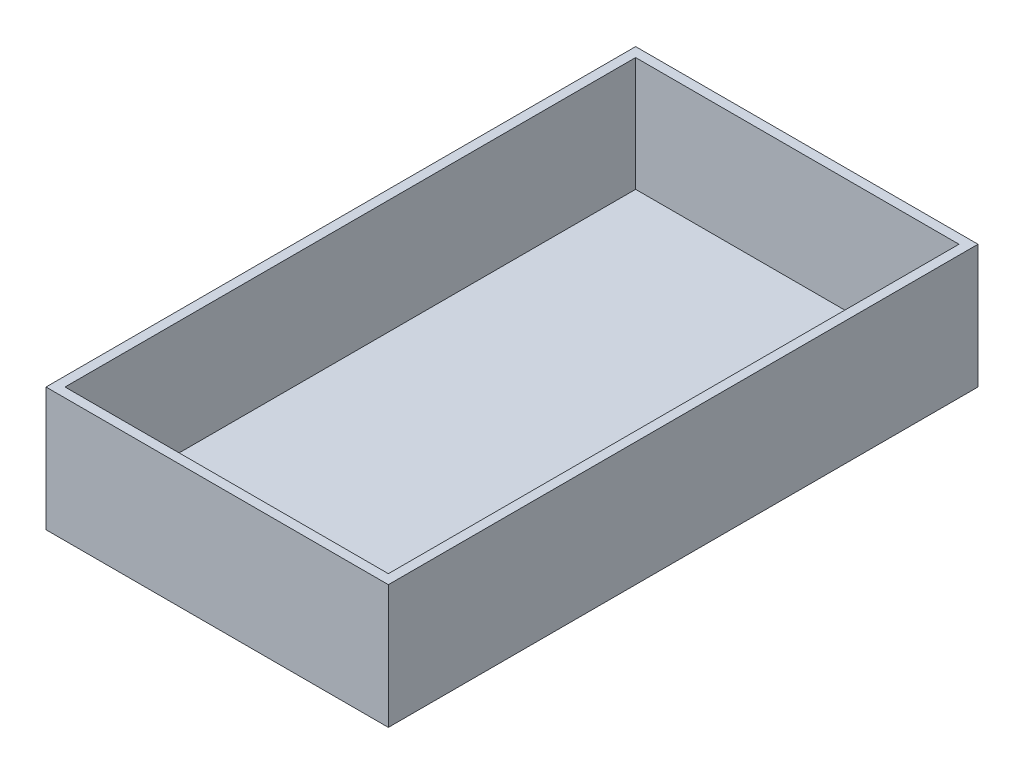
SolidWorks part; units mm, degrees
ref_plane "Front Plane" through (0, 0, 0) normal (0, 0, 1) x (1, 0, 0)
ref_plane "Top Plane" through (0, 0, 0) normal (0, 1, 0) x (1, 0, 0)
ref_plane "Right Plane" through (0, 0, 0) normal (1, 0, 0) x (0, 0, -1)
sketch "Sketch1" plane through (0, 0, 0) normal (0, 1, 0) x (1, 0, 0)
  line L1 (-9000, 15500) -> (9000, 15500)
  line L2 (-9000, 15500) -> (-9000, 15000)
  line L3 (-9000, 15000) -> (9000, 15000)
  line L4 (9000, 15500) -> (9000, 15000)
  line L5 (-9000, 15000) -> (-8500, 15000)
  line L6 (-9000, 15000) -> (-9000, -15000)
  line L7 (-9000, -15000) -> (-8500, -15000)
  line L8 (-8500, 15000) -> (-8500, -15000)
  line L9 (8500, 15000) -> (9000, 15000)
  line L10 (8500, 15000) -> (8500, -15000)
  line L11 (8500, -15000) -> (9000, -15000)
  line L12 (9000, 15000) -> (9000, -15000)
  line L13 (-9000, -15000) -> (9000, -15000)
  line L14 (-9000, -15000) -> (-9000, -15500)
  line L15 (-9000, -15500) -> (9000, -15500)
  line L16 (9000, -15000) -> (9000, -15500)
  point P16 (9000, -15250)
  dimension "D1" = 30000
  dimension "D2" = 17000
  dimension "D3" = 0
  dimension "D4" = 0
  dimension "D5" = 0
  dimension "D6" = 0
  dimension "D7" = 500
  dimension "D8" = 500
  dimension "D9" = 500
  dimension "D10" = 500
  dimension "D11" = 0
extrude "Boss-Extrude2" add sketch "Sketch1" along normal blind 6000 contours L8 L7 L6 L5 | L15 L16 L13 L14 | L10 L11 L12 L9 | L1 L4 L3 L2
sketch "Sketch2" plane through (0, 0, 15500) normal (0, 0, 1) x (1, 0, 0)
  line L1 (-9000, 0) -> (9000, 0)
  line L2 (-9000, 0) -> (-9000, -500)
  line L3 (-9000, -500) -> (9000, -500)
  line L4 (9000, 0) -> (9000, -500)
  dimension "D1" = 500
extrude "Boss-Extrude3" add sketch "Sketch2" against normal up to surface (31000 mm away) up to face at (0, 3000, -15500)
